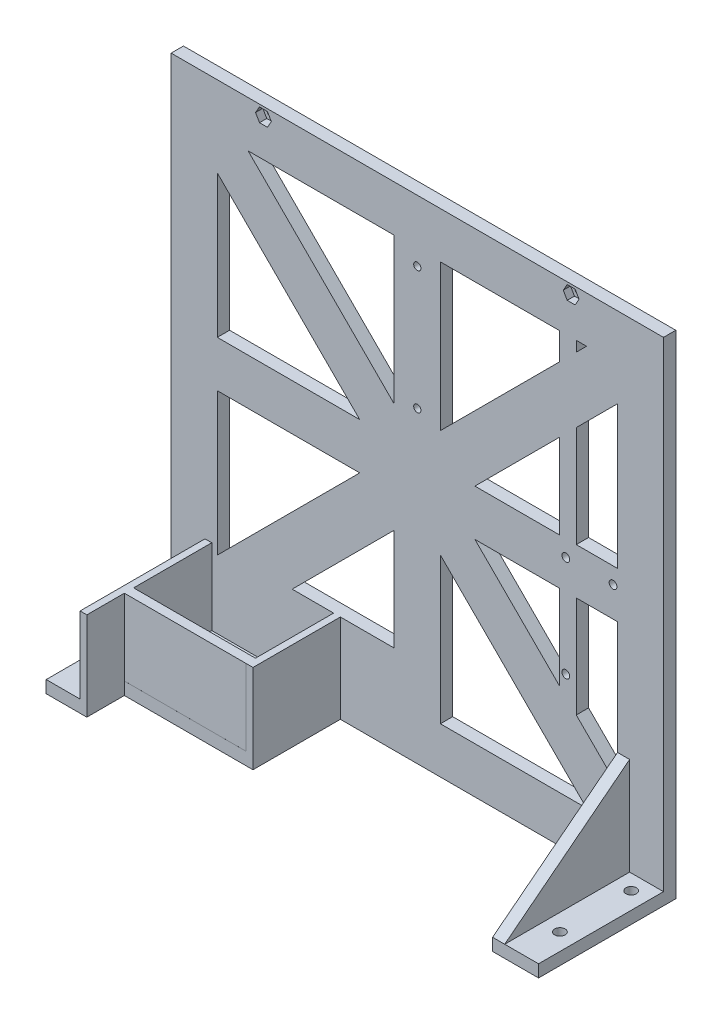
SolidWorks part; units mm, degrees
ref_plane "Front" through (0, 0, 0) normal (0, 0, 1) x (1, 0, 0)
ref_plane "Top" through (0, 0, 0) normal (0, 1, 0) x (1, 0, 0)
ref_plane "Right" through (0, 0, 0) normal (1, 0, 0) x (0, 0, -1)
sketch "Sketch1" plane through (0, 0, 0) normal (0, 0, 1) x (1, 0, 0)
  line L1 (-101.6, 101.6) -> (101.6, 101.6)
  line L2 (-101.6, 101.6) -> (-101.6, -101.6)
  line L3 (-101.6, -101.6) -> (101.6, -101.6)
  line L4 (101.6, 101.6) -> (101.6, -101.6)
  line L5 (-101.6, 101.6) -> (101.6, -101.6) construction
  line L6 (-101.6, -101.6) -> (101.6, 101.6) construction
  line L7 (0, -55) -> (0, 55) construction
  line L10 (-9.525, -22.8914) -> (-9.525, -65.024)
  line L17 (9.525, 22.225) -> (69.85, 82.55)
  line L18 (9.525, 82.55) -> (9.525, 22.225)
  line L19 (69.85, 82.55) -> (9.525, 82.55)
  line L23 (23.7658, 9.525) -> (82.55, 9.525)
  line L24 (23.7658, -9.525) -> (82.55, -9.525)
  line L25 (23.7658, 9.525) -> (82.55, 68.3092)
  line L26 (23.7658, -9.525) -> (82.55, -68.3092)
  line L27 (82.55, 9.525) -> (82.55, 68.3092)
  line L28 (82.55, -9.525) -> (82.55, -68.3092)
  line L29 (9.525, -22.225) -> (69.85, -82.55)
  line L30 (69.85, -82.55) -> (9.525, -82.55)
  line L31 (9.525, -82.55) -> (9.525, -22.225)
  line L32 (0, -101.6) -> (0, 101.6) construction
  line L36 (-82.55, -9.525) -> (-82.55, -68.3092)
  line L37 (-82.55, 9.525) -> (-82.55, 68.3092)
  line L38 (-23.7658, -9.525) -> (-82.55, -68.3092)
  line L39 (-23.7658, 9.525) -> (-82.55, 68.3092)
  line L40 (-23.7658, -9.525) -> (-82.55, -9.525)
  line L41 (-23.7658, 9.525) -> (-82.55, 9.525)
  line L42 (-69.85, 82.55) -> (-9.525, 82.55)
  line L43 (-9.525, 82.55) -> (-9.525, 22.225)
  line L44 (-9.525, 22.225) -> (-69.85, 82.55)
  line L45 (-9.525, -65.024) -> (-51.6576, -65.024)
  line L46 (-51.6576, -65.024) -> (-9.525, -22.8914)
  line L48 (58.7581, 87.2082) -> (65.6057, 87.2082)
  line L49 (58.7581, 87.2082) -> (58.7581, 4.2426)
  line L50 (58.7581, 4.2426) -> (65.6057, 4.2426)
  line L51 (65.6057, 87.2082) -> (65.6057, 4.2426)
  line L56 (58.7581, -5.8139) -> (65.6057, -5.8139)
  line L57 (58.7581, -5.8139) -> (58.7581, -58.6102)
  line L58 (58.7581, -58.6102) -> (65.6057, -58.6102)
  line L59 (65.6057, -5.8139) -> (65.6057, -58.6102)
  line L68 (17.8657, -18.1904) -> (38.0182, -38.3429) construction
  line L70 (90.1937, 58.9244) -> (90.1937, 51.0678)
  line L72 (0, 58.9244) -> (0, 51.0678)
  circle A0 centre (0, 76.2) radius 1.5
  circle A2 centre (0, 25.4) radius 1.5
  circle A3 centre (-63.5, 97.79) radius 1.5
  circle A4 centre (63.5, 97.79) radius 1.5
  point P0 (0, 0)
  dimension "D3" = 3
  dimension "D4" = 50.8
  dimension "D6" = 19.05
  dimension "D7" = 3
  dimension "D9" = 63.5
  dimension "D1" = 203.2
  dimension "D2" = 203.2
  dimension "D5" = 25.4
  dimension "D8" = 3.81
  dimension "D10" = 19.05
  dimension "D11" = 19.05
  dimension "D12" = 19.05
  dimension "D13" = 19.05
  dimension "D14" = 19.05
  dimension "D15" = 9.525
  dimension "D16" = 36.576
  dimension "D17" = 31.75
extrude "Boss-Extrude1" add sketch "Sketch1" along normal blind 5.08
sketch "Sketch2" plane through (0, 0, 5.08) normal (0, 0, 1) x (1, 0, 0)
  line L0 (-101.6, -101.6) -> (101.6, -101.6) construction
  line L2 (-101.6, -101.6) -> (-101.6, -96.52)
  line L5 (-9.525, -65.024) -> (-51.6576, -65.024) construction
  line L13 (-101.6, -101.6) -> (-31.75, -101.6)
  line L17 (-87.63, -65.024) -> (-84.836, -65.024)
  line L18 (-84.836, -96.4094) -> (-84.836, -65.024)
  line L23 (-84.836, -96.4094) -> (-34.544, -96.4094)
  line L24 (-101.6, -96.52) -> (-87.63, -96.52)
  line L25 (-87.63, -96.52) -> (-87.63, -65.024)
  line L28 (-34.544, -96.4094) -> (-34.544, -65.024)
  line L29 (-34.544, -65.024) -> (-31.75, -65.024)
  line L30 (-31.75, -65.024) -> (-31.75, -101.6)
  line L31 (101.6, -101.6) -> (87.63, -101.6)
  line L32 (101.6, -101.6) -> (101.6, -96.52)
  line L33 (101.6, -96.52) -> (87.63, -96.52)
  line L34 (87.63, -101.6) -> (87.63, -96.52)
  dimension "D1" = 5.08
  dimension "D2" = 50.292
  dimension "D4" = 13.97
  dimension "D5" = 2.794
  dimension "D6" = 2.794
  dimension "D8" = 31.3854
extrude "Boss-Extrude2" add sketch "Sketch2" along normal blind 51.562
sketch "Sketch3" plane through (0, -96.52, 0) normal (0, 1, 0) x (1, 0, 0)
  line L0 (-101.6, 0) -> (101.6, 0) construction
  line L2 (-87.63, -56.642) -> (-87.63, -5.08) construction
  line L4 (0, -55) -> (0, 55) construction
  line L5 (-101.6, -56.642) -> (-101.6, -5.08) construction
  circle A0 centre (-94.615, -11.43) radius 2.159
  circle A1 centre (94.615, -11.43) radius 2.159
  circle A2 centre (-94.615, -40.84) radius 2.159
  circle A3 centre (94.615, -40.84) radius 2.159
  dimension "D1" = 4.318
  dimension "D4" = 29.41
  dimension "D5" = 4.318
  dimension "D6" = 4.318
  dimension "D7" = 6.985
  dimension "D2" = 11.43
  dimension "D8" = 29.41
  dimension "D3" = 6.985
extrude "Cut-Extrude1" cut sketch "Sketch3" against normal up to next contours A0 | A1 | A3 | A2
sketch "Sketch11" plane through (0, 0, 5.08) normal (0, 0, 1) x (1, 0, 0)
  line L0 (0, -31.1531) -> (0, 31.1531) construction
  line L1 (-61.869, 94.965) -> (-60.238, 97.79)
  line L2 (-60.238, 97.79) -> (-61.869, 100.615)
  line L3 (-61.869, 100.615) -> (-65.131, 100.615)
  line L4 (-65.131, 100.615) -> (-66.762, 97.79)
  line L5 (-66.762, 97.79) -> (-65.131, 94.965)
  line L6 (-65.131, 94.965) -> (-61.869, 94.965)
  line L7 (65.131, 94.965) -> (61.869, 94.965)
  line L8 (66.762, 97.79) -> (65.131, 94.965)
  line L9 (65.131, 100.615) -> (66.762, 97.79)
  line L10 (61.869, 100.615) -> (65.131, 100.615)
  line L11 (60.238, 97.79) -> (61.869, 100.615)
  line L12 (61.869, 94.965) -> (60.238, 97.79)
  circle A0 centre (-63.5, 97.79) radius 1.5 construction
  circle A1 centre (-63.5, 97.79) radius 1.5
  circle A2 centre (-63.5, 97.79) radius 2.825 construction
  circle A3 centre (63.5, 97.79) radius 2.825 construction
  circle A4 centre (63.5, 97.79) radius 1.5
  dimension "D1" = 5.65
extrude "Cut-Extrude4" cut sketch "Sketch11" against normal blind 3
sketch "Sketch12" plane through (-34.544, 0, 0) normal (-1, 0, 0) x (0, 0, 1)
  line L0 (56.642, -96.52) -> (5.08, -96.52) construction
  line L1 (41.148, -96.52) -> (37.338, -96.52)
  line L2 (41.148, -96.52) -> (41.148, -65.024)
  line L3 (41.148, -65.024) -> (37.338, -65.024)
  line L4 (37.338, -96.52) -> (37.338, -65.024)
  line L5 (56.642, -65.024) -> (5.08, -65.024) construction
  line L6 (5.08, 101.6) -> (5.08, -96.52) construction
  dimension "D1" = 3.81
  dimension "D2" = 32.258
extrude "Boss-Extrude3" add sketch "Sketch12" along normal up to next
sketch "Sketch14" plane through (-31.75, 0, 0) normal (1, 0, 0) x (0, 0, -1)
  line L0 (-56.642, -65.024) -> (-5.08, -65.024) construction
  line L1 (-56.642, -101.6) -> (-41.152, -101.6)
  line L2 (-56.642, -101.6) -> (-56.642, -65.024)
  line L3 (-56.642, -65.024) -> (-41.152, -65.024)
  line L4 (-41.152, -101.6) -> (-41.152, -65.024)
  dimension "D1" = 15.49
extrude "Cut-Extrude5" cut sketch "Sketch14" against normal up to surface (53.086 mm away) up to face at (-84.836, -80.7167, 48.895)
sketch "Sketch15" plane through (0, 0, 5.08) normal (0, 0, 1) x (1, 0, 0)
  line L0 (61.2852, -38.9377) -> (80.7852, -38.9377) construction
  line L5 (61.2852, -38.9377) -> (61.2852, 2.7864) construction
  line L6 (61.2852, 2.7864) -> (80.7852, 2.7864) construction
  line L7 (80.7852, -38.9377) -> (80.7852, 2.7864) construction
  circle A4 centre (61.2852, 2.7864) radius 1.6
  circle A5 centre (80.7852, 2.7864) radius 1.6
  circle A6 centre (80.7852, -38.9377) radius 1.6
  circle A7 centre (61.2852, -38.9377) radius 1.6
  dimension "D8" = 3.2
  dimension "D9" = 3.2
  dimension "D10" = 3.2
  dimension "D7" = 19.5
  dimension "D11" = 41.7241
extrude "Cut-Extrude6" cut sketch "Sketch15" against normal blind 10
sketch "Sketch16" plane through (0, 0, 0) normal (0, 0, -1) x (-1, 0, 0)
  line L1 (-1.5877, 73.45) -> (1.5877, 73.45)
  line L2 (1.5877, 73.45) -> (3.1754, 76.2)
  line L3 (3.1754, 76.2) -> (1.5877, 78.95)
  line L4 (1.5877, 78.95) -> (-1.5877, 78.95)
  line L5 (-1.5877, 78.95) -> (-3.1754, 76.2)
  line L6 (-3.1754, 76.2) -> (-1.5877, 73.45)
  line L25 (-3.1754, 25.4) -> (-1.5877, 22.65)
  line L26 (-1.5877, 22.65) -> (1.5877, 22.65)
  line L27 (1.5877, 22.65) -> (3.1754, 25.4)
  line L28 (3.1754, 25.4) -> (1.5877, 28.15)
  line L29 (1.5877, 28.15) -> (-1.5877, 28.15)
  line L30 (-1.5877, 28.15) -> (-3.1754, 25.4)
  line L31 (-64.4606, 2.7864) -> (-62.8729, 0.0364)
  line L32 (-62.8729, 0.0364) -> (-59.6975, 0.0364)
  line L33 (-59.6975, 0.0364) -> (-58.1097, 2.7864)
  line L34 (-58.1097, 2.7864) -> (-59.6975, 5.5364)
  line L35 (-59.6975, 5.5364) -> (-62.8729, 5.5364)
  line L36 (-62.8729, 5.5364) -> (-64.4606, 2.7864)
  line L37 (-83.9606, 2.7864) -> (-82.3729, 0.0364)
  line L38 (-82.3729, 0.0364) -> (-79.1975, 0.0364)
  line L39 (-79.1975, 0.0364) -> (-77.6097, 2.7864)
  line L40 (-77.6097, 2.7864) -> (-79.1975, 5.5364)
  line L41 (-79.1975, 5.5364) -> (-82.3729, 5.5364)
  line L42 (-82.3729, 5.5364) -> (-83.9606, 2.7864)
  line L43 (-64.4606, -38.9377) -> (-62.8729, -41.6877)
  line L44 (-62.8729, -41.6877) -> (-59.6975, -41.6877)
  line L45 (-59.6975, -41.6877) -> (-58.1097, -38.9377)
  line L46 (-58.1097, -38.9377) -> (-59.6975, -36.1877)
  line L47 (-59.6975, -36.1877) -> (-62.8729, -36.1877)
  line L48 (-62.8729, -36.1877) -> (-64.4606, -38.9377)
  circle A0 centre (0, 76.2) radius 2.75 construction
  circle A4 centre (0, 25.4) radius 2.75 construction
  circle A5 centre (-61.2852, 2.7864) radius 2.75 construction
  circle A6 centre (-80.7852, 2.7864) radius 2.75 construction
  circle A7 centre (-61.2852, -38.9377) radius 2.75 construction
  point P127 (0, 0)
  point P136 (0, 0)
  dimension "D1" = 5.5
extrude "Cut-Extrude7" cut sketch "Sketch16" against normal blind 2.3
sketch "Sketch17" plane through (101.6, 0, 0) normal (1, 0, 0) x (0, 0, -1)
  line L0 (-56.642, -96.52) -> (-5.08, -56.2524)
  line L1 (-5.08, 101.6) -> (-5.08, -96.52) construction
  line L2 (-5.08, -56.2524) -> (-5.08, -96.52)
  line L3 (-56.642, -101.6) -> (0, -101.6) construction
  line L4 (-5.08, -96.52) -> (-56.642, -96.52)
  line L5 (-56.642, -96.52) -> (-5.08, -96.52)
  line L6 (-56.642, -96.52) -> (-56.642, -101.6)
  line L7 (-56.642, -101.6) -> (-5.08, -101.6)
  line L8 (-5.08, -96.52) -> (-5.08, -101.6)
  line M6 (-5.08, 101.6) -> (-5.08, -96.52)
  line M7 (-5.08, -96.52) -> (-56.642, -96.52)
  line M8 (-56.642, -96.52) -> (-56.642, -101.6)
  line M9 (-56.642, -101.6) -> (0, -101.6)
extrude "Boss-Extrude5" add sketch "Sketch17" against normal blind 5 from surface at -13.97 contours L0 M7 M6 | L8 M7 M8 M9 starting at face at (87.63, -99.06, 30.861)
